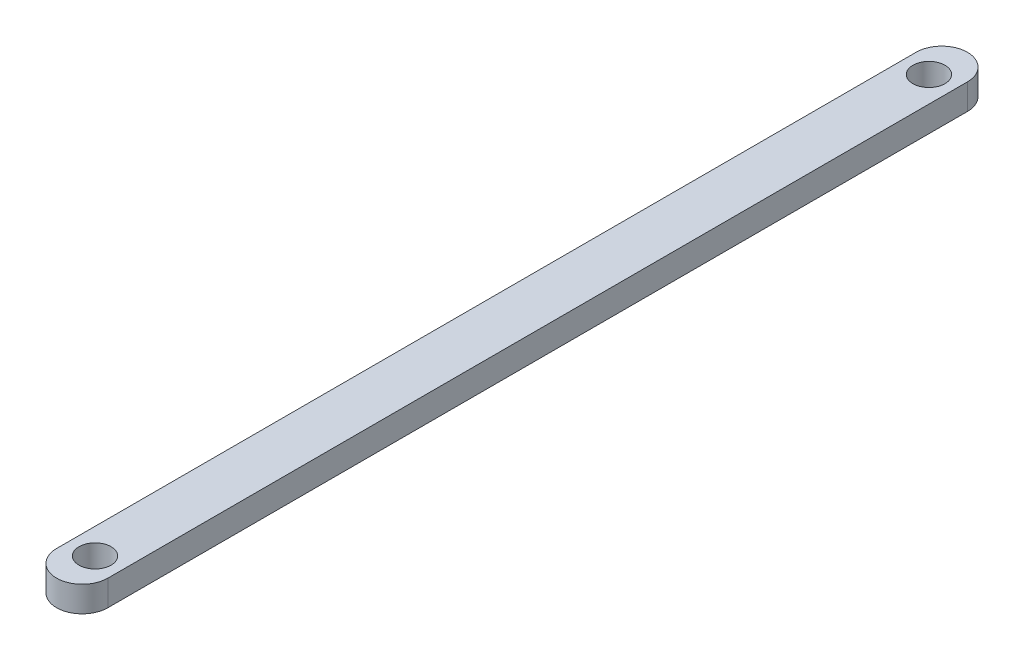
SolidWorks part; units mm, degrees
ref_plane "Front Plane" through (0, 0, 0) normal (0, 0, 1) x (1, 0, 0)
ref_plane "Top Plane" through (0, 0, 0) normal (0, 1, 0) x (1, 0, 0)
ref_plane "Right Plane" through (0, 0, 0) normal (1, 0, 0) x (0, 0, -1)
sketch "Sketch1" plane through (0, 0, 0) normal (0, 1, 0) x (1, 0, 0)
  line L2 (-1.5, 33.5) -> (-1.5, -33.5)
  line L4 (2.5, 33.5) -> (2.5, -33.5)
  circle A0 centre (0.5, 32.5) radius 1.25
  circle A1 centre (0.5, -32.5) radius 1.25
  arc A2 (2.5, 33.5) -> (-1.5, 33.5) centre (0.5, 33.5) ccw
  arc A4 (-1.5, -33.5) -> (2.5, -33.5) centre (0.5, -33.5) ccw
  point P0 (0, 0)
  point P14 (-0.0724, -31.5651)
  dimension "D3" = 2
  dimension "D1" = 2.5
  dimension "D2" = 2.5
  dimension "D4" = 2
  dimension "D5" = 2
extrude "Boss-Extrude1" add sketch "Sketch1" along normal mid plane 2
